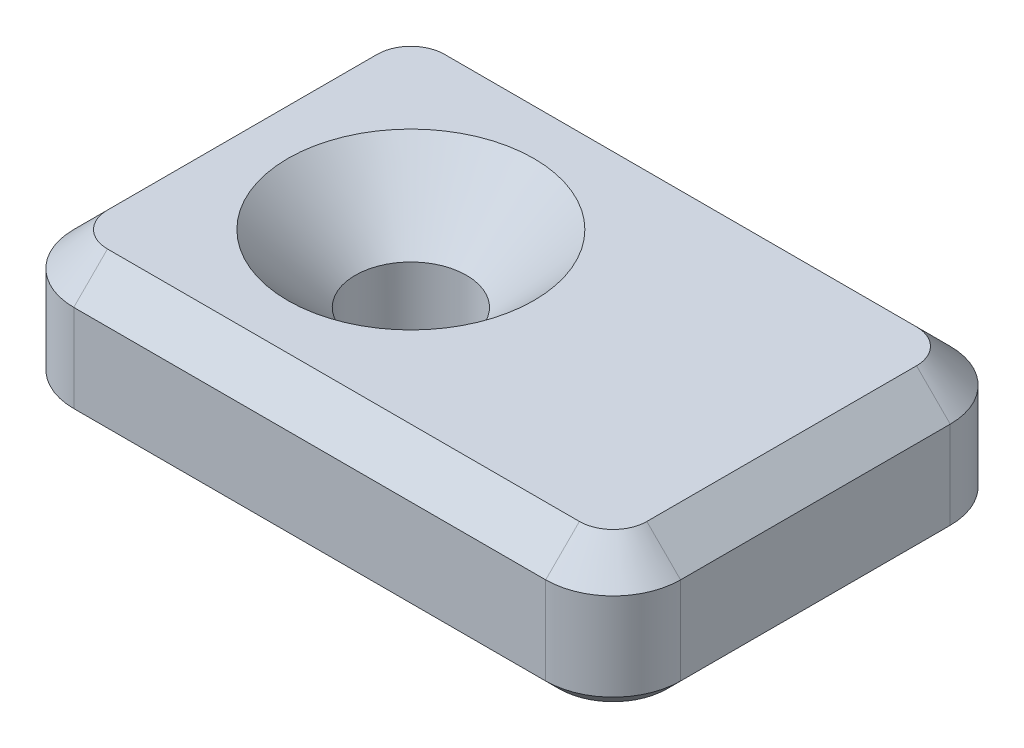
SolidWorks part; units mm, degrees
ref_plane "前视基准面" through (0, 0, 0) normal (0, 0, 1) x (1, 0, 0)
ref_plane "上视基准面" through (0, 0, 0) normal (0, 1, 0) x (1, 0, 0)
ref_plane "右视基准面" through (0, 0, 0) normal (1, 0, 0) x (0, 0, -1)
other "Configuration Table"
sketch "草图1" plane through (0, 0, 0) normal (0, 1, 0) x (1, 0, 0)
  line L1 (2, 0) -> (16, 0)
  line L2 (0, 2) -> (0, 10)
  line L3 (2, 12) -> (16, 12)
  line L4 (18, 2) -> (18, 10)
  circle A0 centre (6, 6) radius 1.65
  arc A1 (16, 12) -> (18, 10) centre (16, 10) cw
  arc A2 (16, 0) -> (18, 2) centre (16, 2) ccw
  arc A3 (2, 0) -> (0, 2) centre (2, 2) cw
  arc A4 (0, 10) -> (2, 12) centre (2, 10) cw
  point P9 (18, 12)
  point P14 (0, 0)
  point P17 (0, 12)
  dimension "D4" = 3.3
  dimension "D5" = 2
  dimension "D1" = 12
  dimension "D2" = 18
  dimension "D3" = 6
extrude "凸台-拉伸1" add sketch "草图1" along normal blind 4
chamfer "倒角1" distance 2 angle 45 1 edges at (6, 4, -4.35)
chamfer "倒角2" distance 1 angle 45 8 edges at (18, 4, -6) (17.4142, 4, -11.4142) (17.4142, 4, -0.5858) (9, 4, -12) (9, 4, 0) (0.5858, 4, -11.4142) (0.5858, 4, -0.5858) (0, 4, -6)
chamfer "倒角3" distance 0.4 angle 45 8 edges at (9, 0, -12) (0.5858, 0, -11.4142) (17.4142, 0, -11.4142) (0, 0, -6) (18, 0, -6) (0.5858, 0, -0.5858) (17.4142, 0, -0.5858) (9, 0, 0)
equation "\"D2@草图1\"=12+6"
